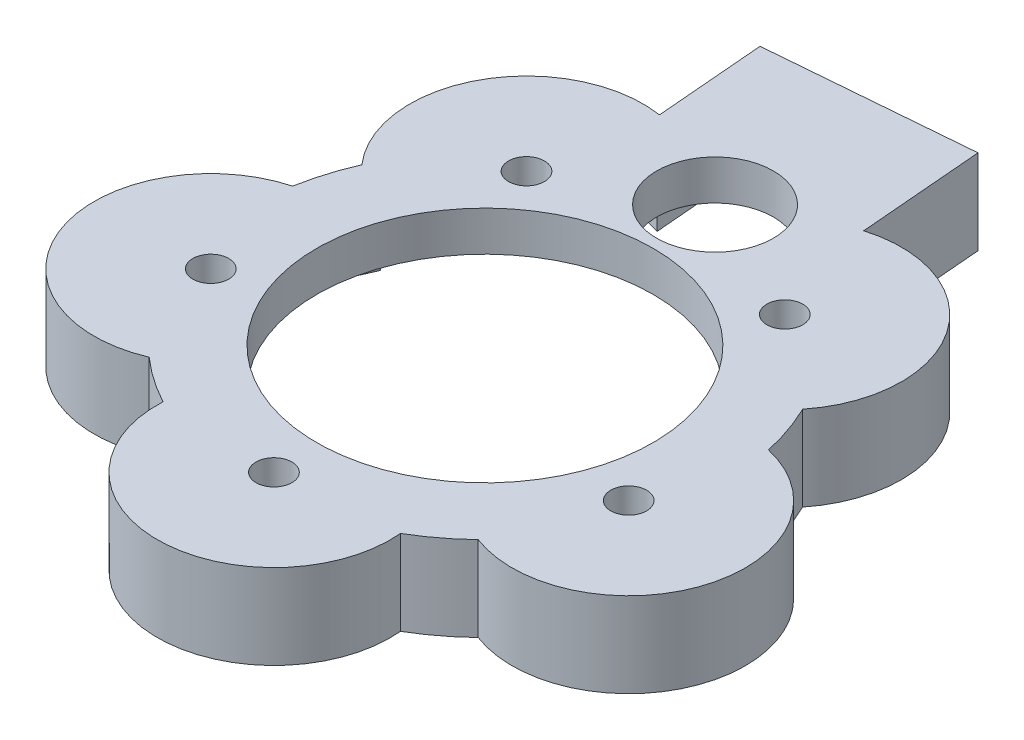
SolidWorks part; units mm, degrees
ref_plane "Front Plane" through (0, 0, 0) normal (0, 0, 1) x (1, 0, 0)
ref_plane "Top Plane" through (0, 0, 0) normal (0, 1, 0) x (1, 0, 0)
ref_plane "Right Plane" through (0, 0, 0) normal (1, 0, 0) x (0, 0, -1)
sketch "Sketch2" plane through (0, -277.7406, 0) normal (0, 1, 0) x (1, 0, 0)
  line L3 (-12.2855, 100.7627) -> (-50.3917, 97.5952)
  line L4 (-12.2855, 100.7627) -> (-50.3917, 97.5952) construction
  line L5 (-50.3917, 97.5952) -> (-48.5145, 75.0118)
  line L6 (-50.3917, 97.5952) -> (-48.5145, 75.0118) construction
  line L7 (-10.1164, 74.6673) -> (-12.2855, 100.7627)
  line L8 (-10.1164, 74.6673) -> (-12.2855, 100.7627) construction
  line L9 (-53.8784, 103.3261) -> (-51.8473, 78.891)
  line L10 (-53.8784, 103.3261) -> (-51.8473, 78.891)
  line L11 (-6.7237, 79.2711) -> (-9.0331, 107.0537)
  line L12 (-6.7237, 79.2711) -> (-9.0331, 107.0537)
  line L13 (-9.0331, 107.0537) -> (-53.8784, 103.3261)
  line L14 (-9.0331, 107.0537) -> (-53.8784, 103.3261)
  circle A0 centre (-55.7838, 53.1908) radius 4
  circle A1 centre (0.6321, 54.3333) radius 4
  circle A4 centre (19.1522, 1.0318) radius 4
  circle A5 centre (-25.8176, -33.053) radius 4
  circle A6 centre (-72.1305, -0.817) radius 4
  circle A7 centre (-25.8176, -33.053) radius 4 construction
  circle A9 centre (-28.3452, 67.7689) radius 13
  arc A10 (-48.5145, 75.0118) -> (-71.8086, 36.6922) centre (-55.7838, 53.1908) ccw
  arc A11 (-71.8086, 36.6922) -> (-76.3165, 21.7989) centre (-26.7895, 14.9372) ccw
  arc A12 (-76.3165, 21.7989) -> (-61.3914, -21.1559) centre (-72.1305, -0.817) ccw
  arc A13 (-61.3914, -21.1559) -> (-48.6201, -30.0453) centre (-26.7895, 14.9372) ccw
  arc A14 (-48.6201, -30.0453) -> (-3.1556, -29.1245) centre (-25.8176, -33.053) ccw
  arc A15 (-3.1556, -29.1245) -> (9.2454, -19.7253) centre (-26.7895, 14.9372) ccw
  arc A16 (9.2454, -19.7253) -> (22.419, 23.7986) centre (19.1522, 1.0318) ccw
  arc A17 (22.419, 23.7986) -> (17.3118, 38.4971) centre (-26.7895, 14.9372) ccw
  arc A18 (17.3118, 38.4971) -> (-10.1164, 74.6673) centre (0.6321, 54.3333) ccw
  arc A20 (-48.5145, 75.0118) -> (-71.8086, 36.6922) centre (-55.7838, 53.1908) ccw construction
  arc A21 (-71.8086, 36.6922) -> (-76.3165, 21.7989) centre (-26.7895, 14.9372) ccw construction
  arc A22 (-76.3165, 21.7989) -> (-61.3914, -21.1559) centre (-72.1305, -0.817) ccw construction
  arc A23 (-61.3914, -21.1559) -> (-48.6201, -30.0453) centre (-26.7895, 14.9372) ccw construction
  arc A24 (-48.6201, -30.0453) -> (-3.1556, -29.1245) centre (-25.8176, -33.053) ccw construction
  arc A25 (-3.1556, -29.1245) -> (9.2454, -19.7253) centre (-26.7895, 14.9372) ccw construction
  arc A26 (9.2454, -19.7253) -> (22.419, 23.7986) centre (19.1522, 1.0318) ccw construction
  arc A27 (22.419, 23.7986) -> (17.3118, 38.4971) centre (-26.7895, 14.9372) ccw construction
  arc A28 (17.3118, 38.4971) -> (-10.1164, 74.6673) centre (0.6321, 54.3333) ccw construction
  circle A30 centre (-26.7895, 14.9372) radius 37.5
  circle A31 centre (-26.7895, 14.9372) radius 37.5 construction
  arc A32 (-75.3798, 36.1029) -> (-78.9614, 24.2697) centre (-26.7895, 14.9372) ccw
  arc A33 (-78.9614, 24.2697) -> (-61.9345, -24.7343) centre (-72.1305, -0.817) ccw
  arc A34 (-61.9345, -24.7343) -> (-51.7872, -31.7973) centre (-26.7895, 14.9372) ccw
  arc A35 (-51.7872, -31.7973) -> (0.0799, -30.7468) centre (-25.8176, -33.053) ccw
  arc A36 (0.0799, -30.7468) -> (9.9329, -23.2788) centre (-26.7895, 14.9372) ccw
  arc A37 (9.9329, -23.2788) -> (24.9617, 26.3744) centre (19.1522, 1.0318) ccw
  arc A38 (24.9617, 26.3744) -> (20.9039, 38.0529) centre (-26.7895, 14.9372) ccw
  arc A39 (20.9039, 38.0529) -> (-6.7237, 79.2711) centre (0.6321, 54.3333) ccw
  arc A41 (-51.8473, 78.891) -> (-75.3798, 36.1029) centre (-55.7838, 53.1908) ccw
  arc A42 (-75.3798, 36.1029) -> (-78.9614, 24.2697) centre (-26.7895, 14.9372) ccw
  arc A43 (-78.9614, 24.2697) -> (-61.9345, -24.7343) centre (-72.1305, -0.817) ccw
  arc A44 (-61.9345, -24.7343) -> (-51.7872, -31.7973) centre (-26.7895, 14.9372) ccw
  arc A45 (-51.7872, -31.7973) -> (0.0799, -30.7468) centre (-25.8176, -33.053) ccw
  arc A46 (0.0799, -30.7468) -> (9.9329, -23.2788) centre (-26.7895, 14.9372) ccw
  arc A47 (9.9329, -23.2788) -> (24.9617, 26.3744) centre (19.1522, 1.0318) ccw
  arc A48 (24.9617, 26.3744) -> (20.9039, 38.0529) centre (-26.7895, 14.9372) ccw
  arc A49 (20.9039, 38.0529) -> (-6.7237, 79.2711) centre (0.6321, 54.3333) ccw
  arc A51 (-51.8473, 78.891) -> (-75.3798, 36.1029) centre (-55.7838, 53.1908) ccw
  point P53 (-22.9381, 72.0266)
  dimension "D3" = 26
  dimension "D1" = 0
  dimension "D2" = 0
extrude "Boss-Extrude1" add sketch "Sketch2" along normal up to surface (8.9 mm away)
sketch "Sketch3" plane through (0, -277.7406, 0) normal (0, -1, 0) x (1, 0, 0)
  line L3 (-51.8473, -78.891) -> (-53.8784, -103.3261)
  line L4 (-51.8473, -78.891) -> (-53.8784, -103.3261)
  line L5 (-9.0331, -107.0537) -> (-6.7237, -79.2711)
  line L6 (-9.0331, -107.0537) -> (-6.7237, -79.2711)
  line L7 (-53.8784, -103.3261) -> (-9.0331, -107.0537)
  line L8 (-53.8784, -103.3261) -> (-9.0331, -107.0537)
  line L9 (-50.3917, -97.5952) -> (-12.2855, -100.7627)
  line L10 (-50.3917, -97.5952) -> (-12.2855, -100.7627)
  line L11 (-48.5145, -75.0118) -> (-50.3917, -97.5952)
  line L12 (-48.5145, -75.0118) -> (-50.3917, -97.5952)
  line L13 (-12.2855, -100.7627) -> (-10.1164, -74.6673)
  line L14 (-12.2855, -100.7627) -> (-10.1164, -74.6673)
  arc A10 (-78.9614, -24.2697) -> (-75.3798, -36.1029) centre (-26.7895, -14.9372) ccw
  arc A11 (-61.9345, 24.7343) -> (-78.9614, -24.2697) centre (-72.1305, 0.817) ccw
  arc A12 (-51.7872, 31.7973) -> (-61.9345, 24.7343) centre (-26.7895, -14.9372) ccw
  arc A13 (0.0799, 30.7468) -> (-51.7872, 31.7973) centre (-25.8176, 33.053) ccw
  arc A14 (9.9329, 23.2788) -> (0.0799, 30.7468) centre (-26.7895, -14.9372) ccw
  arc A15 (24.9617, -26.3744) -> (9.9329, 23.2788) centre (19.1522, -1.0318) ccw
  arc A16 (20.9039, -38.0529) -> (24.9617, -26.3744) centre (-26.7895, -14.9372) ccw
  arc A17 (-6.7237, -79.2711) -> (20.9039, -38.0529) centre (0.6321, -54.3333) ccw
  arc A19 (-75.3798, -36.1029) -> (-51.8473, -78.891) centre (-55.7838, -53.1908) ccw
  arc A20 (-78.9614, -24.2697) -> (-75.3798, -36.1029) centre (-26.7895, -14.9372) ccw
  arc A21 (-61.9345, 24.7343) -> (-78.9614, -24.2697) centre (-72.1305, 0.817) ccw
  arc A22 (-51.7872, 31.7973) -> (-61.9345, 24.7343) centre (-26.7895, -14.9372) ccw
  arc A23 (0.0799, 30.7468) -> (-51.7872, 31.7973) centre (-25.8176, 33.053) ccw
  arc A24 (9.9329, 23.2788) -> (0.0799, 30.7468) centre (-26.7895, -14.9372) ccw
  arc A25 (24.9617, -26.3744) -> (9.9329, 23.2788) centre (19.1522, -1.0318) ccw
  arc A26 (20.9039, -38.0529) -> (24.9617, -26.3744) centre (-26.7895, -14.9372) ccw
  arc A27 (-6.7237, -79.2711) -> (20.9039, -38.0529) centre (0.6321, -54.3333) ccw
  arc A29 (-75.3798, -36.1029) -> (-51.8473, -78.891) centre (-55.7838, -53.1908) ccw
  arc A30 (-71.8086, -36.6922) -> (-48.5145, -75.0118) centre (-55.7838, -53.1908) ccw
  arc A31 (-76.3165, -21.7989) -> (-71.8086, -36.6922) centre (-26.7895, -14.9372) ccw
  arc A32 (-61.3914, 21.1559) -> (-76.3165, -21.7989) centre (-72.1305, 0.817) ccw
  arc A33 (-48.6201, 30.0453) -> (-61.3914, 21.1559) centre (-26.7895, -14.9372) ccw
  arc A34 (-3.1556, 29.1245) -> (-48.6201, 30.0453) centre (-25.8176, 33.053) ccw
  arc A35 (9.2454, 19.7253) -> (-3.1556, 29.1245) centre (-26.7895, -14.9372) ccw
  arc A36 (22.419, -23.7986) -> (9.2454, 19.7253) centre (19.1522, -1.0318) ccw
  arc A37 (17.3118, -38.4971) -> (22.419, -23.7986) centre (-26.7895, -14.9372) ccw
  arc A38 (-10.1164, -74.6673) -> (17.3118, -38.4971) centre (0.6321, -54.3333) ccw
  arc A40 (-71.8086, -36.6922) -> (-48.5145, -75.0118) centre (-55.7838, -53.1908) ccw
  arc A41 (-76.3165, -21.7989) -> (-71.8086, -36.6922) centre (-26.7895, -14.9372) ccw
  arc A42 (-61.3914, 21.1559) -> (-76.3165, -21.7989) centre (-72.1305, 0.817) ccw
  arc A43 (-48.6201, 30.0453) -> (-61.3914, 21.1559) centre (-26.7895, -14.9372) ccw
  arc A44 (-3.1556, 29.1245) -> (-48.6201, 30.0453) centre (-25.8176, 33.053) ccw
  arc A45 (9.2454, 19.7253) -> (-3.1556, 29.1245) centre (-26.7895, -14.9372) ccw
  arc A46 (22.419, -23.7986) -> (9.2454, 19.7253) centre (19.1522, -1.0318) ccw
  arc A47 (17.3118, -38.4971) -> (22.419, -23.7986) centre (-26.7895, -14.9372) ccw
  arc A48 (-10.1164, -74.6673) -> (17.3118, -38.4971) centre (0.6321, -54.3333) ccw
  dimension "D1" = 0
  dimension "D2" = 0
extrude "Boss-Extrude2" add sketch "Sketch3" along normal up to surface (10 mm away)
